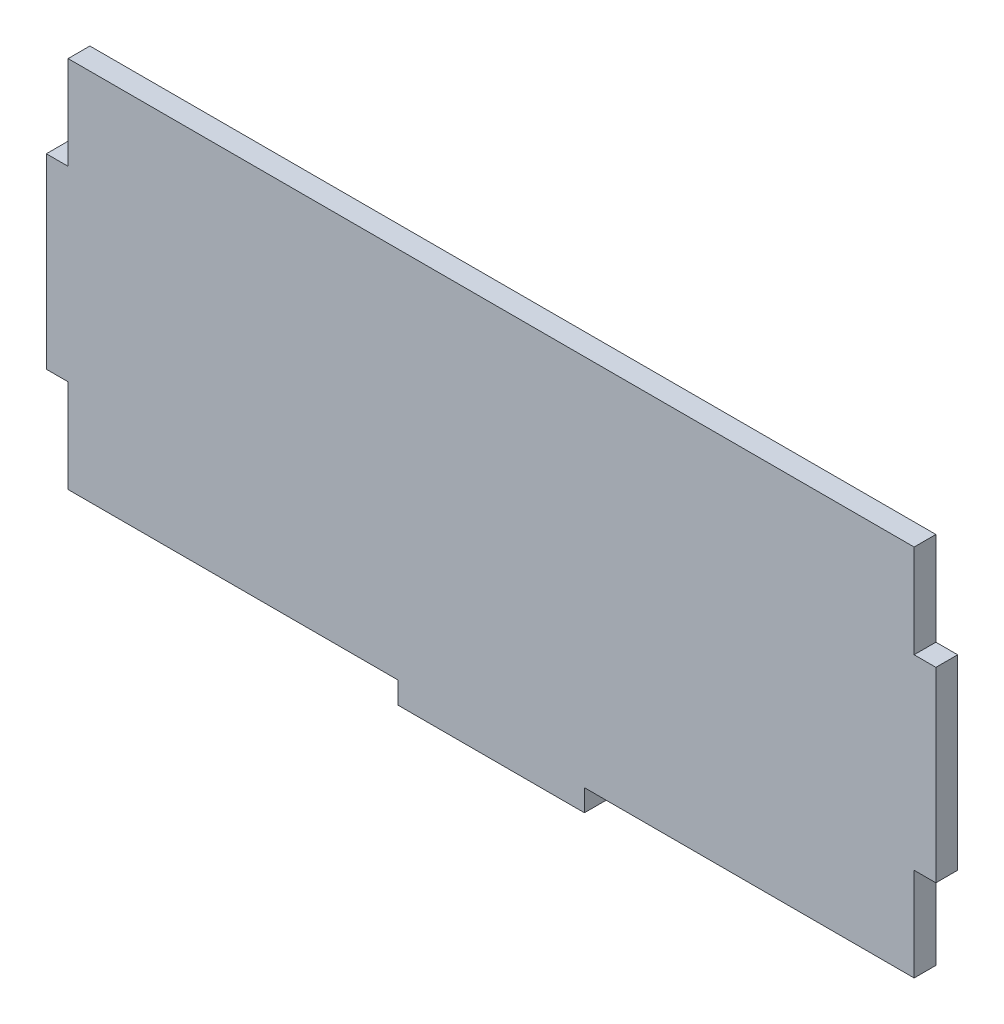
SolidWorks part; units mm, degrees
ref_plane "Спереди" through (0, 0, 0) normal (0, 0, 1) x (1, 0, 0)
ref_plane "Сверху" through (0, 0, 0) normal (0, 1, 0) x (1, 0, 0)
ref_plane "Справа" through (0, 0, 0) normal (1, 0, 0) x (0, 0, -1)
sketch "Эскиз1" plane through (0, 0, 0) normal (0, 0, 1) x (1, 0, 0)
  line L0 (68, 0) -> (68, 60) construction
  line L1 (0, 0) -> (136, 0)
  line L2 (0, 0) -> (0, 60)
  line L3 (0, 60) -> (136, 60)
  line L4 (136, 0) -> (136, 60)
  line L5 (0, 45) -> (-3.5, 45)
  line L6 (0, 45) -> (0, 15)
  line L7 (0, 15) -> (-3.5, 15)
  line L8 (-3.5, 45) -> (-3.5, 15)
  line L9 (68, -3.5) -> (68, 0) construction
  line L10 (53, 0) -> (83, 0)
  line L11 (53, 0) -> (53, -3.5)
  line L12 (53, -3.5) -> (83, -3.5)
  line L13 (83, 0) -> (83, -3.5)
  line L14 (0, 30) -> (-3.5, 30) construction
  line L15 (136, 15) -> (139.5, 15)
  line L16 (139.5, 45) -> (139.5, 15)
  line L17 (136, 45) -> (139.5, 45)
  line L18 (136, 45) -> (136, 15)
  dimension "D1" = 136
  dimension "D2" = 60
  dimension "D3" = 30
  dimension "D4" = 30
  dimension "D5" = 3.5
  dimension "D6" = 3.5
extrude "Бобышка-Вытянуть1" add sketch "Эскиз1" along normal blind 3.5 contours L1 L4 L3 L2 | L5 L8 L7 L2 | L17 L4 L15 L16 | L13 L1 L11 L12
